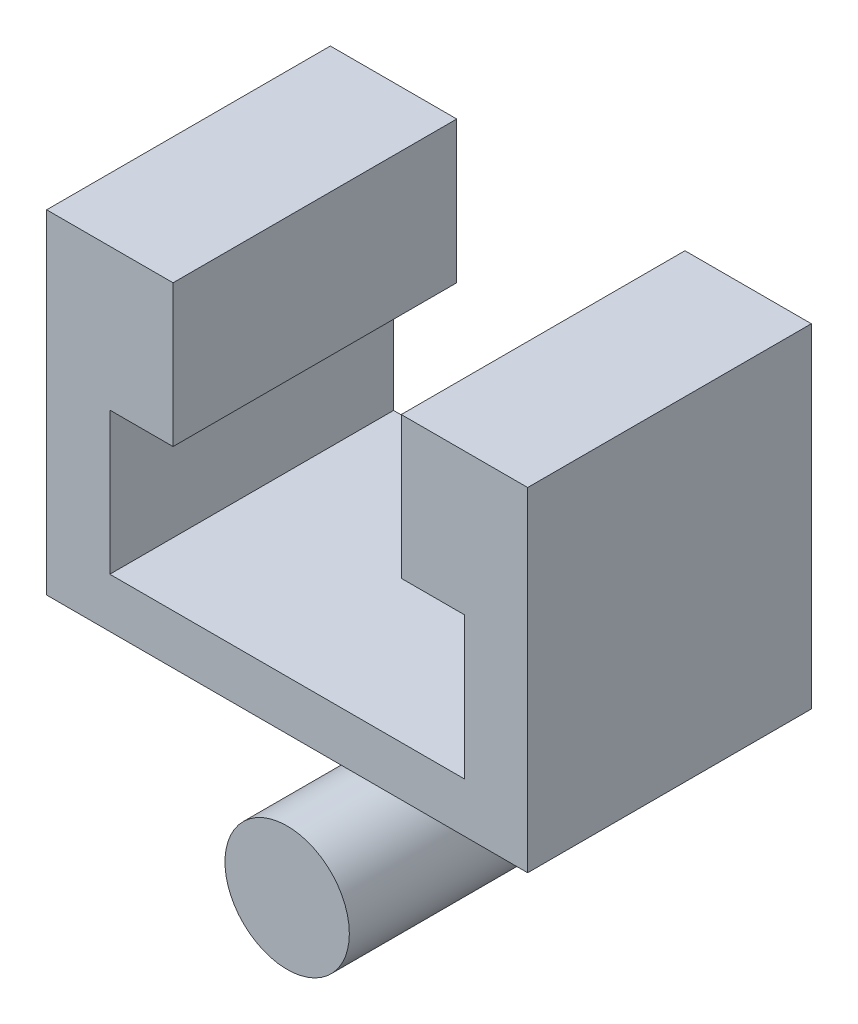
SolidWorks part; units mm, degrees
material "ASTM A36 Steel"
ref_plane "Front Plane" through (0, 0, 0) normal (0, 0, 1) x (1, 0, 0)
ref_plane "Top Plane" through (0, 0, 0) normal (0, 1, 0) x (1, 0, 0)
ref_plane "Right Plane" through (0, 0, 0) normal (1, 0, 0) x (0, 0, -1)
sketch "Sketch1" plane through (0, 0, 0) normal (0, 0, 1) x (1, 0, 0)
  line L0 (-11.1361, 0) -> (-11.1361, 25.4)
  line L1 (-11.1361, 25.4) -> (11.1361, 25.4)
  line L2 (11.1361, 25.4) -> (11.1361, 0)
  arc A0 (11.1361, 0) -> (-11.1361, 0) centre (0, 0) ccw
  arc A1 (11.1361, 0) -> (-11.1361, 0) centre (0, 0) ccw
  dimension "D1" = 22.2722
  dimension "D2" = 25.4
extrude "Boss-Extrude1" add sketch "Sketch1" along normal blind 0.8406 contours A1 L0 L1 L2
sketch "Sketch2" plane through (0, 0, 0) normal (0, 0, 1) x (1, 0, 0)
  circle A0 centre (0, 0) radius 11.1361
  dimension "D1" = 22.2722
extrude "Boss-Extrude2" add sketch "Sketch2" along normal blind 50.8
sketch "Sketch3" plane through (0, 0, 0) normal (0, 0, 1) x (1, 0, 0)
  line L0 (-43.0685, 25.4) -> (43.0685, 25.4)
  line L1 (43.0685, 25.4) -> (43.0685, 85.1481)
  line L2 (43.0685, 85.1481) -> (-43.0685, 85.1481)
  line L3 (-43.0685, 85.1481) -> (-43.0685, 25.4)
  point P3 (0, 25.4)
  dimension "D1" = 86.137
  dimension "D2" = 59.7481
extrude "Boss-Extrude3" add sketch "Sketch3" along normal blind 50.8
sketch "Sketch4" plane through (0, 0, 50.8) normal (0, 0, 1) x (1, 0, 0)
  line L0 (20.4315, 85.1481) -> (20.4315, 59.7481)
  line L1 (43.0685, 85.1481) -> (-43.0685, 85.1481) construction
  line L2 (20.4315, 59.7481) -> (31.75, 59.7481)
  line L3 (31.75, 59.7481) -> (31.75, 34.29)
  line L4 (31.75, 34.29) -> (-31.75, 34.29)
  line L5 (-31.75, 34.29) -> (-31.75, 59.7481)
  line L6 (-31.75, 59.7481) -> (-20.4315, 59.7481)
  line L7 (-20.4315, 59.7481) -> (-20.4315, 85.1481)
  line L8 (-20.4315, 85.1481) -> (20.4315, 85.1481)
  line L9 (43.0685, 25.4) -> (43.0685, 85.1481) construction
  line L10 (-43.0685, 85.1481) -> (-43.0685, 25.4) construction
  line L12 (-43.0685, 25.4) -> (43.0685, 25.4) construction
  dimension "D1" = 22.637
  dimension "D2" = 11.3185
  dimension "D3" = 11.3185
  dimension "D4" = 22.637
  dimension "D6" = 25.4
  dimension "D7" = 25.4
  dimension "D5" = 8.89
extrude "Cut-Extrude1" cut sketch "Sketch4" against normal through all contours L8 L0 L2 L3 L4 L5 L6 L7
equation "\"F\"= 600'Applied Load [lbf]"
equation "\"P\"= \"F\" / 2'Symmetric Leg Force [lbf]"
equation "\"Ys\"= 36259.43'Material Yield Strength (ASTM A36) [psi]"
equation "\"E\"= 29007547.53'Elastic Modulus (ASTM A36) [psi]"
equation "\"Ns\"= 4'Factor of Safety"
equation "\"sigma_allow\"= \"Ys\" / \"Ns\"'Allowable Bending/Tensile Stress [psi]"
equation "\"delta_max\"= 0.005'Maximum Deflection Limit [in]"
equation "\"L_A\"= 2.00'Feature A Pin Length [in]"
equation "\"d_stress_A\"= ( ( 32 * \"P\" * \"L_A\" ) / ( pi * \"sigma_allow\" ) ) ^ ( 1 / 3 )'Feature A Minimum Stress Diameter [in]"
equation "\"d_stiff_A\"= ( ( 64 * \"P\" * ( \"L_A\" ^ 3 ) ) / ( 3 * pi * \"E\" * \"delta_max\" ) ) ^ ( 1 / 4 )'Feature A Minimum Stiffness Diameter [in]"
equation "\"d_A\"= 1.000'Feature A Selected Nominal Diameter [in]"
equation "\"w_B\"= \"d_A\"'Feature B Width (Tied to Feature A Pin Dia) [in]"
equation "\"L_B\"= 2.00'Feature B Link Length [in]"
equation "\"t_stress_B\"= \"P\" / ( \"w_B\" * \"sigma_allow\" )'Feature B Minimum Tensile Thickness [in]"
equation "\"t_stiff_B\"= ( \"P\" * \"L_B\" ) / ( \"w_B\" * \"E\" * \"delta_max\" )'Feature B Minimum Stiffness Thickness [in]"
equation "\"t_B\"= 0.250'Feature B Selected Nominal Thickness [in]"
equation "\"L_C\"= 2.5'Feature C Beam Span Length [in]"
equation "\"w_C\"= 1.00'Feature C Beam Cross-Section Width [in]"
equation "\"h_stress_C\"= ( ( 1.5 * \"P\" * \"L_C\" ) / ( \"w_C\" * \"sigma_allow\" ) ) ^ ( 1 / 2 )'Feature C Minimum Bending Height [in]"
equation "\"h_stiff_C\"= ( ( \"P\" * ( \"L_C\" ^ 3 ) ) / ( 4 * \"w_C\" * \"E\" * \"delta_max\" ) ) ^ ( 1 / 3 )'Feature C Minimum Stiffness Height [in]"
equation "\"h_C\"= 0.375'Feature C Selected Nominal Height [in]"
equation "\"P_D\"= \"P\" / 2'Feature D Reaction Load from Feature C [lbf]"
equation "\"L_D\"= 2.00'Feature D Web Cantilever Length [in]"
equation "\"w_D\"= 1.00'Feature D Web Width [in]"
equation "\"t_stress_D\"= ( ( 6 * \"P_D\" * \"L_D\" ) / ( \"w_D\" * \"sigma_allow\" ) ) ^ ( 1 / 2 )'Feature D Minimum Bending Thickness [in]"
equation "\"t_stiff_D\"= ( ( 4 * \"P_D\" * ( \"L_D\" ^ 3 ) ) / ( \"w_D\" * \"E\" * \"delta_max\" ) ) ^ ( 1 / 3 )'Feature D Minimum Stiffness Thickness [in]"
equation "\"t_D\"= 0.500'Feature D Selected Nominal Thickness [in]"
equation "\"P_E\"= \"P_D\"'Feature E Transferred Flange Load [lbf]"
equation "\"L_E\"= 2.00'Feature E Flange Overhang Span [in]"
equation "\"w_E\"= 1.00'Feature E Flange Width [in]"
equation "\"h_stress_E\"= ( ( 6 * \"P_E\" * \"L_E\" ) / ( \"w_E\" * \"sigma_allow\" ) ) ^ ( 1 / 2 )'Feature E Minimum Bending Thickness [in]"
equation "\"h_stiff_E\"= ( ( 4 * \"P_E\" * ( \"L_E\" ^ 3 ) ) / ( \"w_E\" * \"E\" * \"delta_max\" ) ) ^ ( 1 / 3 )'Feature E Minimum Stiffness Thickness [in]"
equation "\"h_E\"= 0.500'Feature E Selected Nominal Thickness [in]"
equation "\"D1@Sketch1\"=\"d_stress_A\""
equation "\"D1@Boss-Extrude1\"=\"t_stress_B\""
equation "\"D1@Sketch2\"=\"d_stress_A\""
equation "\"D1@Boss-Extrude2\"=\"L_A\""
equation "\"D1@Sketch3\"=\"L_C\"+2*(\"t_stress_D\")"
equation "\"D2@Sketch3\"=\"h_stress_C\" + \"w_D\"+\"w_E\""
equation "\"D7@Sketch4\"=\"w_E\""
equation "\"D6@Sketch4\"=\"w_E\""
equation "\"D1@Sketch4\"=\"t_stress_D\"+\"h_stress_E\""
equation "\"D4@Sketch4\"=\"t_stress_D\"+\"h_stress_E\""
equation "\"D2@Sketch4\"=\"t_stress_D\""
equation "\"D3@Sketch4\"=\"t_stress_D\""
equation "\"D1@Boss-Extrude3\"=\"L_D\""
